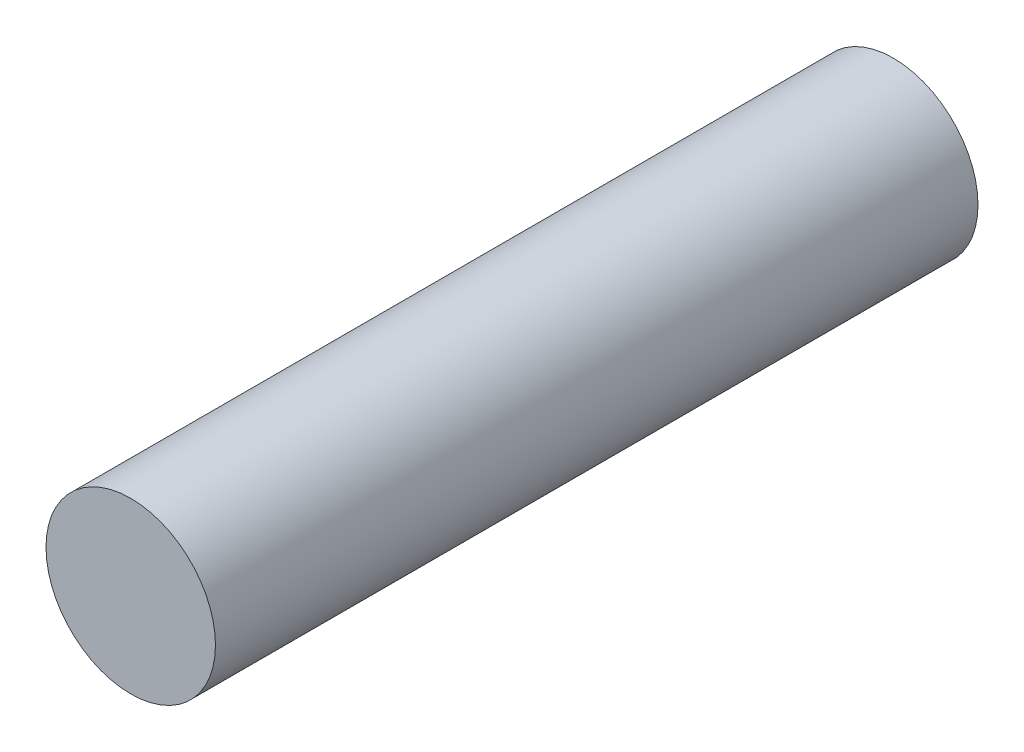
SolidWorks part; units mm, degrees
material "Cast Stainless Steel"
ref_plane "Front Plane" through (0, 0, 0) normal (0, 0, 1) x (1, 0, 0)
ref_plane "Top Plane" through (0, 0, 0) normal (0, 1, 0) x (1, 0, 0)
ref_plane "Right Plane" through (0, 0, 0) normal (1, 0, 0) x (0, 0, -1)
sketch "Sketch1" plane through (0, 0, 0) normal (0, 0, 1) x (1, 0, 0)
  circle A0 centre (0, 0) radius 1
  dimension "D1" = 2
extrude "Boss-Extrude1" add sketch "Sketch1" along normal blind 9
